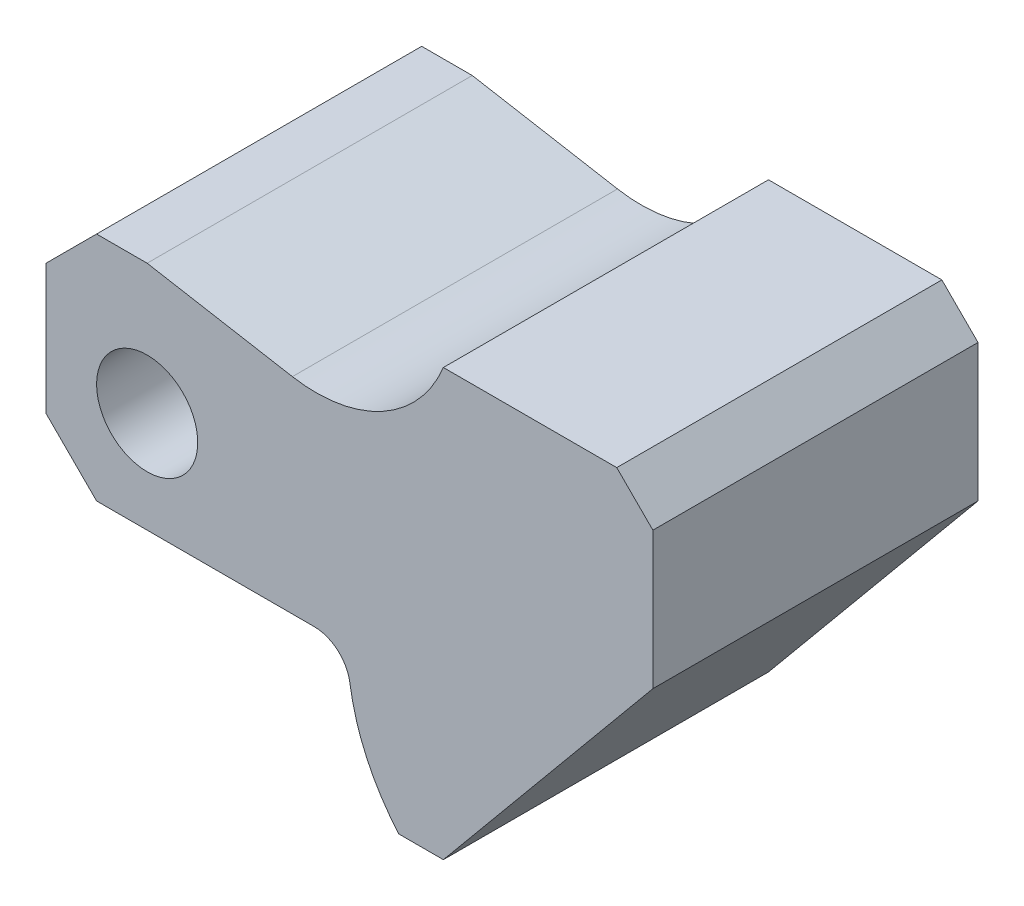
SolidWorks part; units mm, degrees
material "AISI 1020"
ref_plane "Front Plane" through (0, 0, 0) normal (0, 0, 1) x (1, 0, 0)
ref_plane "Top Plane" through (0, 0, 0) normal (0, 1, 0) x (1, 0, 0)
ref_plane "Right Plane" through (0, 0, 0) normal (1, 0, 0) x (0, 0, -1)
sketch "Sketch1" plane through (0, 0, 0) normal (0, 0, 1) x (1, 0, 0)
  line L0 (0, 0) -> (-7, 7)
  line L1 (-7, 7) -> (-7, 25)
  line L2 (-7, 25) -> (0, 32)
  line L6 (77, 35) -> (77, 16)
  line L7 (77, 16) -> (48, -19)
  line L8 (48, -19) -> (41.834, -19)
  line L9 (30.1125, 0) -> (0, 0)
  line L10 (77, 35) -> (72, 40)
  line L11 (72, 40) -> (48, 40)
  line L12 (0, 32) -> (7, 32)
  line L13 (7, 32) -> (27.104, 28.4551)
  line L14 (7, -41.8607) -> (7, 32) construction
  line L15 (29.0896, 14) -> (-34.8822, 14) construction
  arc A2 (41.834, -19) -> (35.0582, -4.2647) centre (63.7429, 0) cw
  arc A4 (35.0582, -4.2647) -> (30.1125, 0) centre (30.1125, -5) ccw
  arc A5 (48, 40) -> (27.104, 28.4551) centre (30.4034, 47.1665) cw
  circle A6 centre (7, 14) radius 7
  point P8 (44.917, -19)
  point P20 (15.0563, 0)
  point P21 (16.2455, 14)
  dimension "D5" = 29
  dimension "D6" = 5
  dimension "D14" = 19
  dimension "D21" = 14
  dimension "D2" = 7
  dimension "D3" = 45
  dimension "D4" = 19
  dimension "D7" = 29
  dimension "D8" = 19
  dimension "D9" = 24
  dimension "D10" = 45
  dimension "D11" = 5
  dimension "D12" = 29
  dimension "D13" = 59
  dimension "D15" = 10
  dimension "D17" = 32
  dimension "D16" = 45
  dimension "D18" = 84
  dimension "D19" = 14
  dimension "D20" = 14
extrude "Boss-Extrude1" add sketch "Sketch1" along normal mid plane 45
equation "\"B\" = 59"
equation "\"A\" = 84"
equation "\"c\" = 45"
equation "\"D1@Boss-Extrude1\"=\"c\""
equation "\"D13@Sketch1\"=\"B\""
equation "\"D18@Sketch1\"=\"A\""
